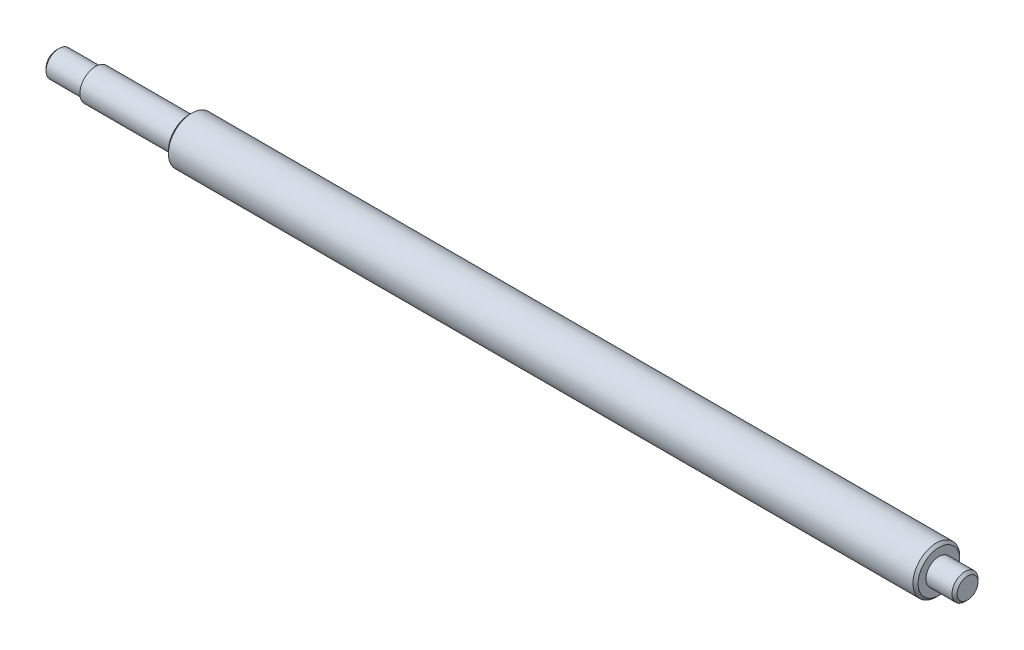
SolidWorks part; units mm, degrees
ref_plane "Front Plane" through (0, 0, 0) normal (0, 0, 1) x (1, 0, 0)
ref_plane "Top Plane" through (0, 0, 0) normal (0, 1, 0) x (1, 0, 0)
ref_plane "Right Plane" through (0, 0, 0) normal (1, 0, 0) x (0, 0, -1)
sketch "Sketch1" plane through (0, 0, 0) normal (0, 1, 0) x (1, 0, 0)
  line L0 (-222.9641, 0) -> (291.446, 0) construction
  line L1 (-208.4669, 0) -> (-208.4669, 4)
  line L2 (-207.4669, 5) -> (-193.4669, 5)
  line L3 (-193.4669, 5) -> (-193.4669, 6)
  line L4 (-193.4669, 6) -> (-157.4669, 6)
  line L5 (-157.4669, 6) -> (-157.4669, 8)
  line L6 (-156.4669, 9) -> (129.5331, 9)
  line L7 (130.5331, 8) -> (130.5331, 5)
  line L8 (130.5331, 5) -> (140.5331, 5)
  line L9 (141.5331, 4) -> (141.5331, 0)
  line L10 (-208.4669, 0) -> (141.5331, 0)
  line L11 (-208.4669, 4) -> (-207.4669, 5)
  line L12 (-157.4669, 8) -> (-156.4669, 9)
  line L13 (140.5331, 5) -> (141.5331, 4)
  line L14 (129.5331, 9) -> (130.5331, 8)
  point P4 (-208.4669, 5)
  point P9 (-157.4669, 9)
  point P10 (130.5331, 9)
  point P12 (141.5331, 5)
  dimension "D1" = 288
  dimension "D2" = 9
  dimension "D3" = 5
  dimension "D4" = 6
  dimension "D5" = 10
  dimension "D6" = 15
  dimension "D7" = 36
  dimension "D8" = 11
revolve "Revolve1" add sketch "Sketch1" angle 360 about L0
sketch "Szkic1" plane through (-208.4669, 0, 0) normal (-1, 0, 0) x (0, 0, 1)
  point P0 (0, 0)
